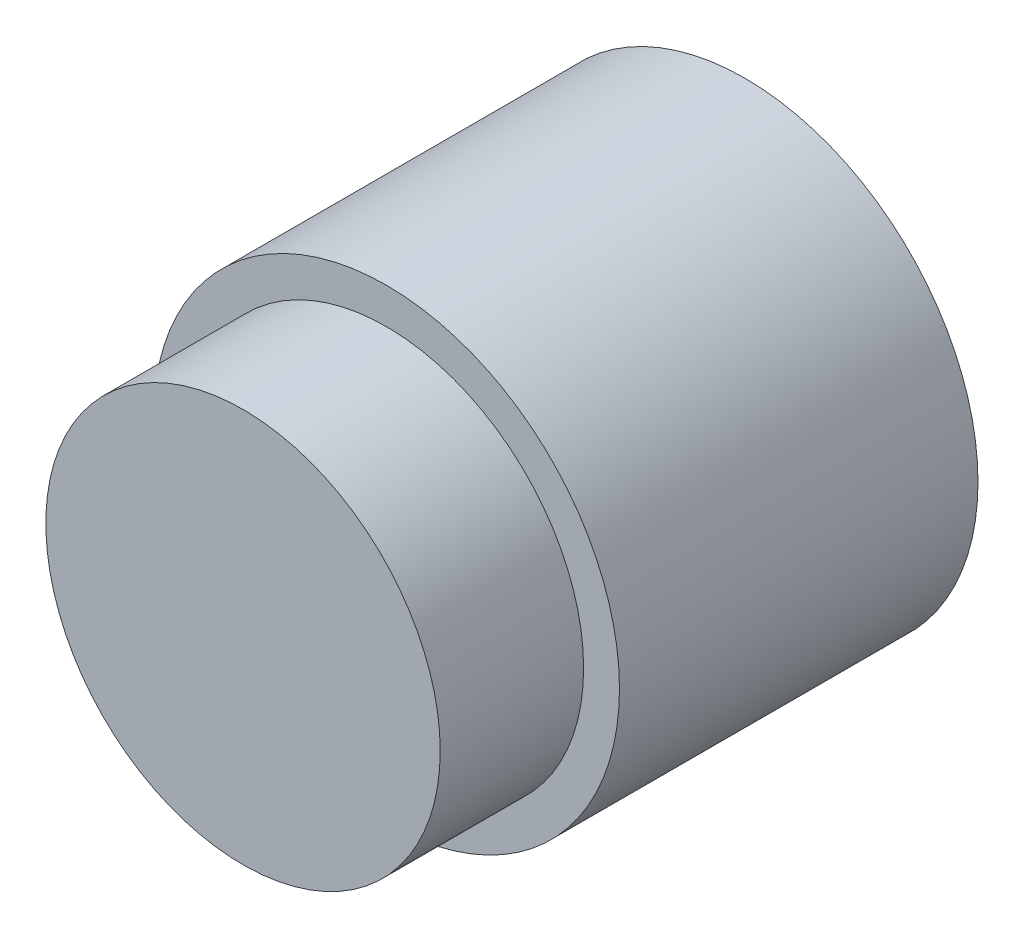
SolidWorks part; units mm, degrees
ref_plane "Plan de face" through (0, 0, 0) normal (0, 0, 1) x (1, 0, 0)
ref_plane "Plan de dessus" through (0, 0, 0) normal (0, 1, 0) x (1, 0, 0)
ref_plane "Plan de droite" through (0, 0, 0) normal (1, 0, 0) x (0, 0, -1)
sketch "Esquisse2" plane through (0, 0, 0) normal (0, 0, 1) x (1, 0, 0)
  circle A0 centre (0, 0) radius 0.65
extrude "Boss.-Extru.1" add sketch "Esquisse2" along normal blind 1
sketch "Esquisse3" plane through (0, 0, 1) normal (0, 0, 1) x (1, 0, 0)
  circle A0 centre (0, 0) radius 0.55
extrude "Boss.-Extru.3" add sketch "Esquisse3" along normal blind 0.4
